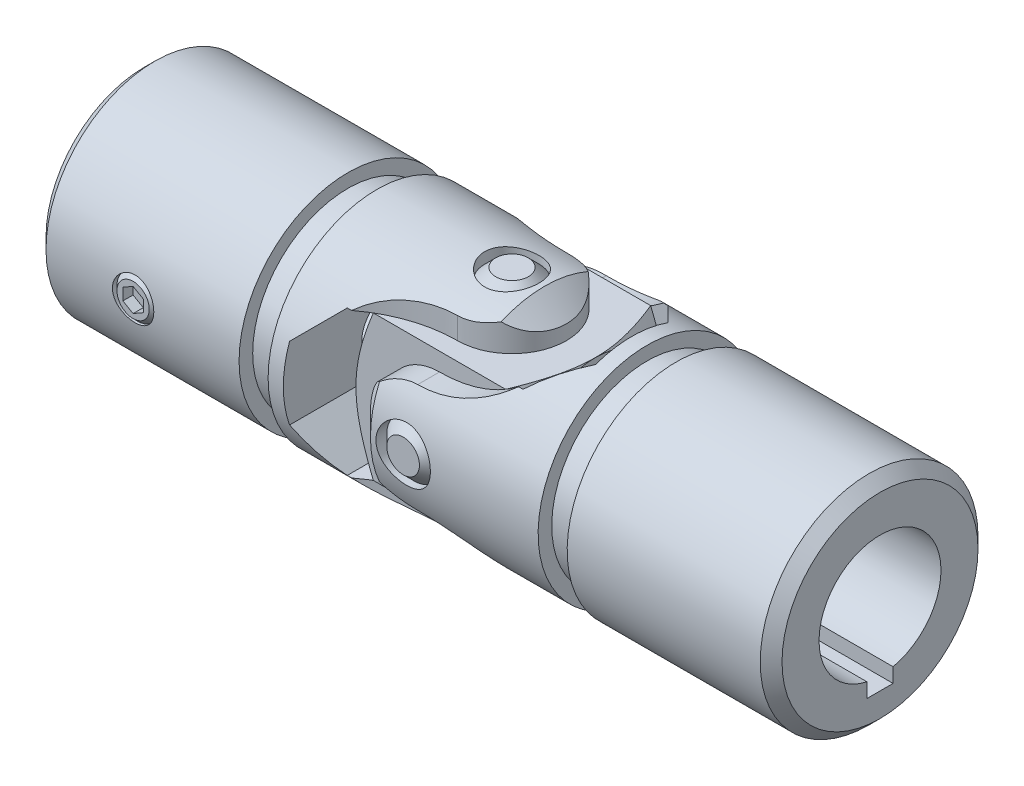
SolidWorks part; units mm, degrees
ref_plane "Front Plane" through (0, 0, 0) normal (0, 0, 1) x (1, 0, 0)
ref_plane "Top Plane" through (0, 0, 0) normal (0, 1, 0) x (1, 0, 0)
ref_plane "Right Plane" through (0, 0, 0) normal (1, 0, 0) x (0, 0, -1)
sketch "Sketch0" plane through (0, 0, 0) normal (0, 1, 0) x (1, 0, 0)
  line L0 (-42.926, 0) -> (42.926, 0) construction
  line L1 (-42.926, 12.7) -> (-42.926, -12.7) construction
  line L2 (-17.526, 7.112) -> (-17.526, -7.112) construction
  line L3 (-17.526, 7.112) -> (-10.414, 0) construction
  line L4 (-10.414, 0) -> (-17.526, -7.112) construction
  line L5 (-13.97, 3.556) -> (-13.97, -3.556) construction
  point P7 (-17.526, 0)
  point P8 (0, 0)
  point P12 (-13.97, 0)
  point P14 (-17.526, 7.112)
  dimension "Overall Length" = 85.852
  dimension "Joint Diameter" = 25.4
  dimension "Bore Dia" = 14.224
  dimension "Bore Depth" = 25.4
sketch "Sketch20" plane through (0, 0, 0) normal (1, 0, 0) x (0, 0, -1)
  line L1 (-5.588, 1.524) -> (-8.636, 1.524)
  line L2 (-5.588, 1.524) -> (-5.588, -1.524)
  line L3 (-5.588, -1.524) -> (-8.636, -1.524)
  line L4 (-8.636, 1.524) -> (-8.636, -1.524)
  line L5 (-5.588, 1.524) -> (-8.636, -1.524) construction
  line L6 (-5.588, -1.524) -> (-8.636, 1.524) construction
  point P0 (-7.112, 0)
  dimension "Keyway Depth" = 1.524
  dimension "Keyway Width" = 3.048
sketch "Sketch1" plane through (0, 0, 0) normal (0, 1, 0) x (1, 0, 0)
  line L0 (-42.926, 12.7) -> (-19.1357, 12.7)
  line L1 (6.35, 12.7) -> (6.35, 0)
  line L2 (6.35, 0) -> (-42.926, 0)
  line L3 (-42.926, 0) -> (-42.926, 12.7)
  line L4 (-42.926, 12.7) -> (-42.926, -12.7) construction
  line L5 (-42.926, 0) -> (42.926, 0) construction
  line L6 (-15.748, 12.7) -> (6.35, 12.7)
  line L7 (-15.748, 3.556) -> (-15.748, 11.1125) construction
  line L8 (-19.1357, 12.7) -> (-19.1357, 11.1125)
  line L9 (-19.1357, 11.1125) -> (-15.748, 11.1125)
  line L10 (-15.748, 12.7) -> (-15.748, 11.1125)
  line L11 (0, 0) -> (12.7, 0) construction
  line L12 (-13.97, 3.556) -> (-17.526, 3.556) construction
  line L13 (-17.526, 7.112) -> (-17.526, -7.112) construction
  circle A0 centre (0, 0) radius 12.7 construction
  dimension "D1" = 3.3877
  dimension "D2" = 1.5875
  dimension "D3" = 49.276
revolve "Revolve1" add sketch "Sketch1" angle 360 about L0
chamfer "Chamfer1" distance 1.27 angle 45 1 edges at (-42.926, 0, 12.7)
chamfer "Chamfer2" distance 2.54 angle 45 1 edges at (6.35, 0, 12.7)
sketch "Sketch2" plane through (0, 0, 0) normal (0, 1, 0) x (1, 0, 0)
  line L0 (-15.748, 12.7) -> (-12.3603, 12.7) construction
  line L1 (-15.748, 12.7) -> (6.35, 12.7) construction
  line L2 (3.81, 12.7) -> (-15.748, 12.7) construction
  line L3 (-19.1357, 11.1125) -> (-15.748, 11.1125) construction
  line L4 (-42.926, 0) -> (6.35, 0) construction
  line L5 (-12.3603, 12.7) -> (12.7, 12.7)
  line L6 (12.7, 12.7) -> (12.7, -12.7)
  line L7 (12.7, -12.7) -> (-12.3603, -12.7)
  line L8 (0, 6.35) -> (0, 0) construction
  arc A0 (-12.3603, 12.7) -> (0, 6.35) centre (0, 21.5546) ccw
  arc A1 (0, -6.35) -> (0, 6.35) centre (0, 0) ccw
  arc A2 (-12.3603, -12.7) -> (0, -6.35) centre (0, -21.5546) cw
  dimension "D1" = 12.7
extrude "Extrude1" cut sketch "Sketch2" against normal through all and the other way through all
sketch "Sketch3" plane through (0, 0, 0) normal (0, 0, 1) x (1, 0, 0)
  line L0 (-9.7409, 8.4582) -> (-13.97, 4.2291)
  line L1 (-9.7409, 8.4582) -> (12.7, 8.4582)
  line L2 (-13.97, 4.2291) -> (-13.97, -4.2291)
  line L3 (-9.7409, -8.4582) -> (12.7, -8.4582)
  line L4 (12.7, 8.4582) -> (12.7, -8.4582)
  line L5 (-13.97, -4.2291) -> (-9.7409, -8.4582)
  dimension "D1" = 16.9164
  dimension "D2" = 4.2291
extrude "Extrude3" cut sketch "Sketch3" against normal through all and the other way through all
sketch "Sketch4" plane through (-42.926, 0, 0) normal (-1, 0, 0) x (0, 0, 1)
  circle A0 centre (0, 0) radius 7.112
extrude "Extrude4" cut sketch "Sketch4" against normal up to vertex (25.4 mm away) up to point (-17.526, 0, -7.112)
sketch "Sketch5" plane through (-17.526, 0, 0) normal (-1, 0, 0) x (0, 0, 1)
  circle A0 centre (0, 0) radius 7.112 construction
  circle A1 centre (0, 0) radius 7.112
extrude "Extrude5" cut sketch "Sketch5" against normal through all draft 45
sketch "Sketch6" plane through (0, 0, 0) normal (0, 1, 0) x (1, 0, 0)
  line L0 (-42.926, 0) -> (42.926, 0) construction
  line L1 (6.35, 0) -> (3.175, 0) construction
  line L2 (3.175, 0) -> (0, 0) construction
  circle A0 centre (0, 0) radius 3.175
  arc A1 (0, -6.35) -> (0, 6.35) centre (0, 0) ccw construction
  dimension "D1" = 6.35
extrude "Extrude6" cut sketch "Sketch6" against normal through all and the other way through all
sketch "Sketch7" plane through (-42.926, 0, 0) normal (-1, 0, 0) x (0, 0, 1)
  line L0 (8.636, 0) -> (7.112, 0) construction
  line L1 (8.636, 1.524) -> (8.636, -1.524)
  line L2 (8.636, 1.524) -> (5.588, 1.524)
  line L3 (5.588, 1.524) -> (5.588, -1.524)
  line L4 (8.636, -1.524) -> (5.588, -1.524)
  line L5 (0, 0) -> (7.112, 0) construction
  line L6 (7.112, 1.524) -> (7.112, -1.524) construction
  circle A0 centre (0, 0) radius 7.112 construction
  circle A1 centre (0, 0) radius 7.112 construction
  point P4 (7.112, 0)
  dimension "Keyway Depth" = 1.524
  dimension "Keyway Width" = 3.048
extrude "Extrude7" cut sketch "Sketch7" against normal up to vertex (25.4 mm away) up to point (-17.526, 0, 0)
sketch "Sketch8" plane through (0, 0, 0) normal (0, 0, 1) x (1, 0, 0)
  line L0 (-42.926, 11.43) -> (-42.926, -11.43) construction
  line L1 (-17.526, 1.524) -> (-42.926, 1.524) construction
  line L2 (-17.526, 1.524) -> (-42.926, 1.524) construction
  circle A0 centre (-31.496, 0) radius 2.413
  point P4 (-29.083, 0)
  dimension "Screw Size" = 4.826
  dimension "D1" = 11.43
  dimension "D3" = 25.4
extrude "Extrude8" cut sketch "Sketch8" along normal through all
sketch "Sketch17" plane through (0, 0, 0) normal (0, 1, 0) x (1, 0, 0)
  line L0 (-31.496, 0) -> (-31.496, -12.7) construction
  line L1 (-33.909, 0) -> (-29.083, 0) construction
  line L2 (-31.496, -12.7) -> (-29.6122, -12.7)
  line L3 (-30.1413, -7.9375) -> (-29.083, -7.9375) construction
  line L4 (-29.083, -7.9375) -> (-29.083, -8.9958) construction
  line L5 (-29.083, -12.1708) -> (-29.083, -12.7) construction
  line L6 (-29.083, -12.7) -> (-29.6122, -12.7) construction
  line L12 (-29.083, -12.7) -> (-19.1357, -12.7) construction
  line L17 (-29.6122, -12.7) -> (-29.083, -12.1708)
  line L18 (-29.083, -12.1708) -> (-29.083, -8.9958)
  line L19 (-29.083, -8.9958) -> (-30.1413, -7.9375)
  line L20 (-30.1413, -7.9375) -> (-30.6705, -7.9375)
  line L21 (-30.6705, -7.9375) -> (-31.496, -8.763)
  line L22 (-31.496, -8.763) -> (-31.496, -12.7)
  line L23 (-30.6705, -7.9375) -> (-31.496, -7.9375) construction
  line L24 (-31.496, -7.9375) -> (-31.496, -8.763) construction
  dimension "Screw Length" = 4.7625
  dimension "D2" = 0.5292
  dimension "D3" = 1.0583
revolve "Revolve2" add sketch "Sketch17" angle 360 about L0
sketch "Sketch9" plane through (0, 0, 12.7) normal (0, 0, 1) x (1, 0, 0)
  line L1 (-31.496, 1.3748) -> (-32.6866, 0.6874)
  line L2 (-32.6866, 0.6874) -> (-32.6866, -0.6874)
  line L3 (-32.6866, -0.6874) -> (-31.496, -1.3748)
  line L4 (-31.496, -1.3748) -> (-30.3054, -0.6874)
  line L5 (-30.3054, -0.6874) -> (-30.3054, 0.6874)
  line L6 (-30.3054, 0.6874) -> (-31.496, 1.3748)
  circle A0 centre (-31.496, 0) radius 1.1906 construction
  dimension "Hex Size" = 2.3813
extrude "Extrude9" cut sketch "Sketch9" against normal blind 1.1906
mirror "Mirror1" about plane through (0, 0, 0) normal (1, 0, 0) of bodies 120 122 109
move or copy body "Body-Move/Copy1" bodies to move or copy 110 123 copy no rotation origin (0, 0, 0) rotation axis (1, 0, 0) rotation angle 90
sketch "Sketch18" plane through (0, 0, 0) normal (0, 1, 0) x (1, 0, 0)
  line L0 (-42.926, -6.9468) -> (-17.526, -6.9468)
  line L1 (-17.526, -6.9468) -> (-17.526, -8.636)
  line L2 (-17.526, -8.636) -> (-42.926, -8.636)
  line L3 (-42.926, 7.112) -> (-17.526, 7.112)
  line L4 (-17.526, 7.112) -> (-17.526, -6.9468)
  line L5 (17.526, 7.112) -> (17.526, -7.112)
  line L6 (17.526, -7.112) -> (42.926, -7.112)
  line L7 (17.526, 7.112) -> (42.926, 7.112)
  line L8 (0, 0) -> (17.526, 0) construction
  line L9 (42.926, -11.43) -> (42.926, 11.43) construction
  line L10 (-42.926, 11.43) -> (-42.926, -11.43) construction
sketch "Sketch10" plane through (0, 0, 0) normal (0, 0, 1) x (1, 0, 0)
  line L0 (-9.7409, 8.4582) -> (9.7409, -8.4582) construction
  line L1 (-9.7409, 8.4582) -> (9.7409, 8.4582)
  line L2 (-9.7409, 8.4582) -> (-9.7409, -8.4582)
  line L3 (-9.7409, -8.4582) -> (9.7409, -8.4582)
  line L4 (9.7409, 8.4582) -> (9.7409, -8.4582)
  line L5 (0, 8.4582) -> (6.35, 8.4582) construction
extrude "Extrude10" add sketch "Sketch10" against normal up to surface and the other way up to surface separate body up to face at (-3.175, 0, -8.4582) other way up to face at (3.175, 0, 8.4582)
sketch "Sketch11" plane through (9.7409, 0, 0) normal (1, 0, 0) x (0, 0, -1)
  line L4 (-8.4582, -8.4582) -> (-8.4582, 8.4582) construction
  circle A0 centre (0, 0) radius 8.4582
extrude "Extrude11" cut sketch "Sketch11" against normal through all draft 60 flip side to cut
sketch "Sketch12" plane through (-9.7409, -21.0185, 0) normal (1, 0, 0) x (0, -1, 0)
  circle A2 centre (-21.0185, 0) radius 8.4582
  circle A6 centre (-21.0185, 0) radius 8.4582
  dimension "D1" = 0
extrude "Extrude12" cut sketch "Sketch12" along normal through all draft 60 flip side to cut
sketch "Sketch13" plane through (0, 0, 0) normal (0, 1, 0) x (1, 0, 0)
  circle A0 centre (0, 0) radius 3.175 construction
  circle A1 centre (0, 0) radius 3.175
extrude "Extrude13" cut sketch "Sketch13" against normal through all and the other way through all
sketch "Sketch14" plane through (0, 0, 0) normal (0, 1, 0) x (1, 0, 0)
  circle A1 centre (0, 0) radius 3.175
  circle A2 centre (0, 0) radius 3.175
  dimension "D1" = 0
extrude "Extrude14" add sketch "Sketch14" along normal mid plane 25.4 separate body
sketch "Sketch15" plane through (0, 0, 0) normal (0, 0, 1) x (1, 0, 0)
  circle A0 centre (0, 0) radius 3.175 construction
  circle A1 centre (0, 0) radius 3.175
extrude "Extrude15" cut sketch "Sketch15" against normal through all and the other way through all
sketch "Sketch16" plane through (0, 0, 0) normal (0, 0, 1) x (1, 0, 0)
  circle A1 centre (0, 0) radius 3.175
  circle A2 centre (0, 0) radius 3.175
  dimension "D1" = 0
extrude "Extrude16" add sketch "Sketch16" along normal mid plane 25.4
chamfer "Chamfer3" distance 1.27 angle 45 4 edges at (0, -12.7, 3.175) (0, 12.7, 3.175) (3.175, 0, 12.7) (3.175, 0, -12.7)
equation "\"D2@Sketch3\" = \"D1@Sketch3\" / 4"
equation "\"D1@Extrude14\" = \"Joint Diameter@Sketch0\""
equation "\"D1@Extrude16\" = \"D1@Extrude14\""
equation "\"D1@Sketch3\" = \"Joint Diameter@Sketch0\"*.666"
equation "\"D2@Sketch3\" = \"D1@Sketch3\"/4"
equation "\"D1@Sketch8\" = \"D3@Sketch8\"*.45"
equation "\"D1@Sketch1\" = \"D3@Sketch1\"*.06875"
equation "\"D1@Extrude9\" = \"Screw Length@Sketch17\"/4"
equation "\"Keyway Depth@Sketch7\"=\"Keyway Depth@Sketch20\""
equation "\"Keyway Width@Sketch7\"=\"Keyway Width@Sketch20\""
